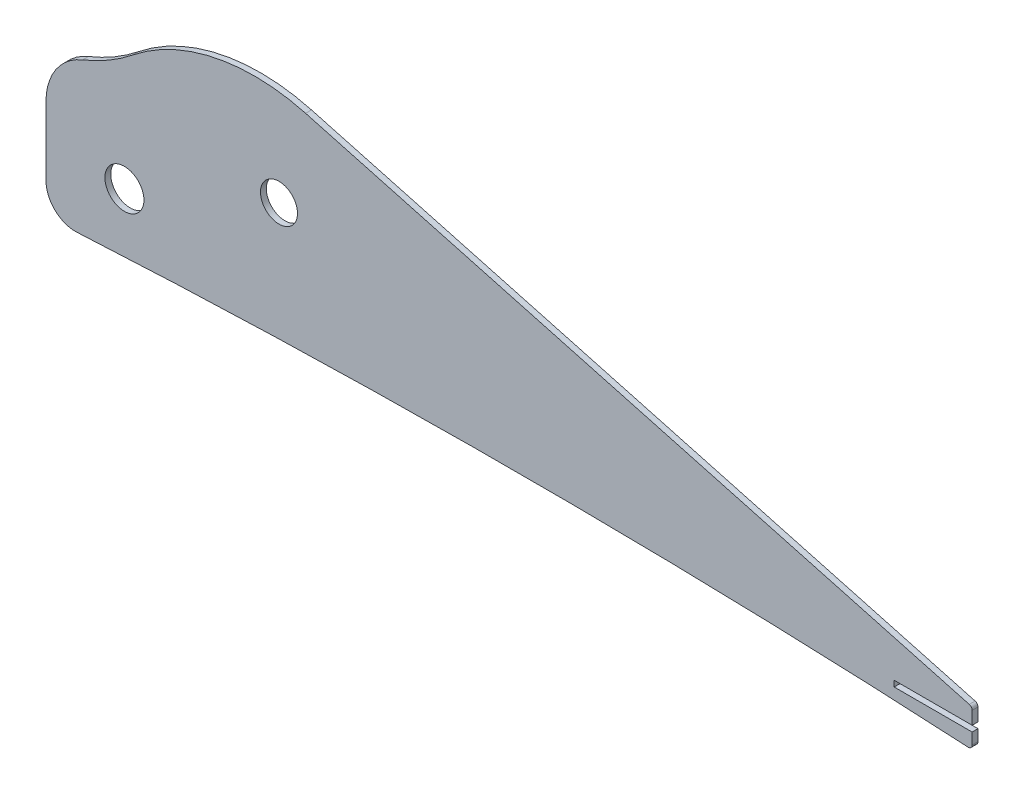
SolidWorks part; units mm, degrees
material "Acrylic (Medium-high impact)"
ref_plane "Front Plane" through (0, 0, 0) normal (0, 0, 1) x (1, 0, 0)
ref_plane "Top Plane" through (0, 0, 0) normal (0, 1, 0) x (1, 0, 0)
ref_plane "Right Plane" through (0, 0, 0) normal (1, 0, 0) x (0, 0, -1)
sketch "Sketch1" plane through (0, 0, 0) normal (0, 0, 1) x (1, 0, 0)
  line L19 (108.1541, 67.5523) -> (448.5237, -24.7969)
  line L21 (-25, -28.9652) -> (-25, 6.2614)
  line L23 (450, -42.1095) -> (450, -26.7272)
  arc A1 (-9.1696, -43.9422) -> (-25, -28.9652) centre (-10, -28.9652) cw
  arc A2 (450, -26.7272) -> (448.5237, -24.7969) centre (448, -26.7272) ccw
  arc A3 (447.8878, -44.1063) -> (450, -42.1095) centre (448, -42.1095) ccw
  arc A4 (-6.2394, 34.0764) -> (19.5157, 49.1416) centre (-44.8529, 129.637) ccw
  arc A5 (108.1541, 67.5523) -> (19.5157, 49.1416) centre (81.9688, -28.9584) ccw
  arc A6 (-6.2394, 34.0764) -> (-25, 6.2614) centre (5, 6.2614) ccw
  arc A8 (-9.1696, -43.9422) -> (447.8878, -44.1063) centre (217.8882, -4139.2319) cw
  point P15 (-50, 61.6833)
  point P16 (24, -21)
  point P24 (450, -25.1975)
  point P26 (64.0016, 21)
  point P30 (433.6267, -34.6874)
  dimension "D3" = 2
  dimension "D4" = 100
  dimension "D5" = 30
  dimension "D2" = 2
  dimension "D1" = 15
extrude "Boss-Extrude1" add sketch "Sketch1" along normal blind 3
sketch "Sketch2" plane through (0, 0, 3) normal (0, 0, 1) x (1, 0, 0)
  circle A4 centre (94.5, 21) radius 9.5
  point P6 (94.5, 21)
  dimension "D1" = 19
extrude "Cut-Extrude2" cut sketch "Sketch2" against normal through all
sketch "Sketch6" plane through (0, 0, 3) normal (0, 0, 1) x (1, 0, 0)
  line L0 (450, -42.1095) -> (450, -26.7272) construction
  line L1 (450, -36.3433) -> (410, -36.3433)
  line L2 (450, -36.3433) -> (450, -33.3433)
  line L3 (450, -33.3433) -> (410, -33.3433)
  line L4 (410, -36.3433) -> (410, -33.3433)
  dimension "D1" = 40
  dimension "D2" = 3
extrude "Cut-Extrude4" cut sketch "Sketch6" against normal through all
sketch "Sketch7" plane through (0, 0, 3) normal (0, 0, 1) x (1, 0, 0)
  circle A0 centre (15.2118, -12.475) radius 10
  dimension "D1" = 20
extrude "Cut-Extrude5" cut sketch "Sketch7" against normal blind 10
